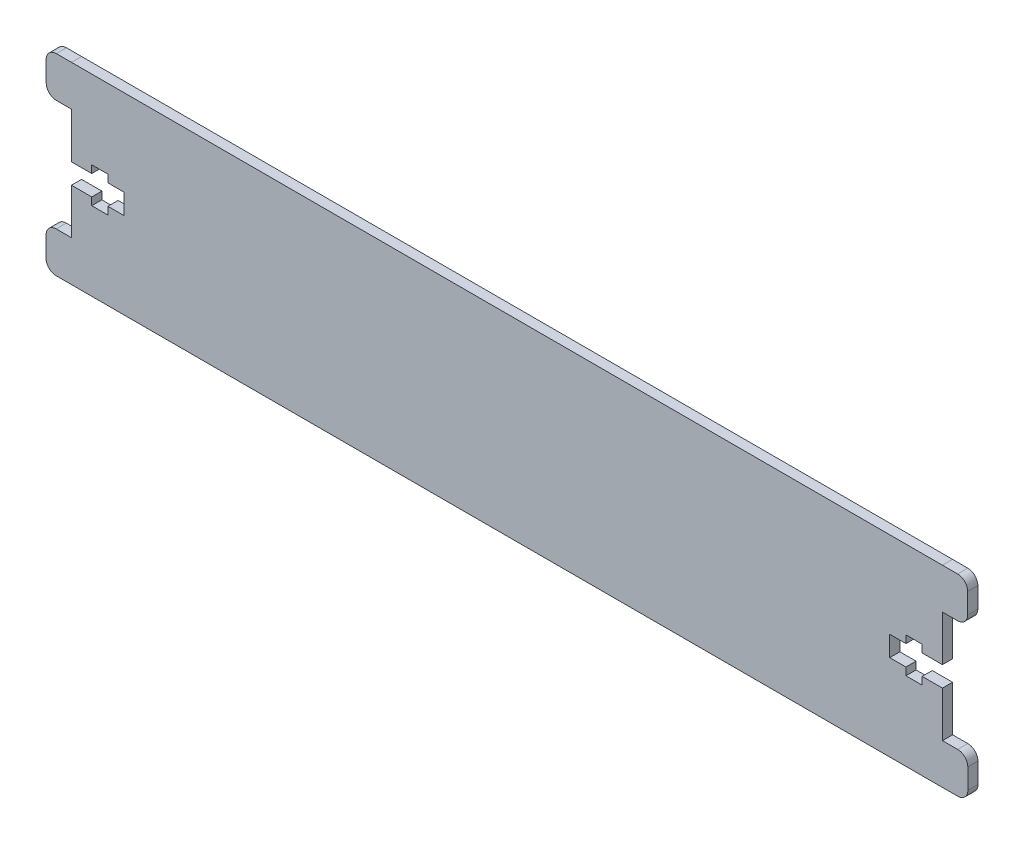
SolidWorks part; units mm, degrees
ref_plane "前视基准面" through (0, 0, 0) normal (0, 0, 1) x (1, 0, 0)
ref_plane "上视基准面" through (0, 0, 0) normal (0, 1, 0) x (1, 0, 0)
ref_plane "右视基准面" through (0, 0, 0) normal (1, 0, 0) x (0, 0, -1)
sketch "草图1" plane through (0, 0, 0) normal (0, 0, 1) x (1, 0, 0)
  line L0 (81.5579, -9.9003) -> (76.5617, -9.9106) construction
  line L1 (81.527, 20.0921) -> (76.5307, 20.0921) construction
  line L2 (81.5436, -5.9003) -> (76.5436, -5.9045)
  line L3 (81.5723, -13.9002) -> (81.5436, -5.9003)
  line L4 (76.5723, -13.9178) -> (81.5723, -13.9002)
  line L5 (66.1319, 5.08) -> (77.8396, 5.0921) construction
  line L6 (76.5319, 7.08) -> (72.5319, 7.08)
  line L7 (72.5319, 7.08) -> (72.5319, 8.58)
  line L8 (72.5319, 8.58) -> (69.3319, 8.58)
  line L9 (69.3319, 8.58) -> (69.3319, 7.08)
  line L10 (69.3319, 7.08) -> (66.1319, 7.08)
  line L11 (69.3319, 1.58) -> (69.3319, 3.08)
  line L12 (72.5319, 3.08) -> (72.5319, 1.58)
  line L13 (69.3319, 3.08) -> (66.1319, 3.08)
  line L14 (72.5319, 1.58) -> (69.3319, 1.58)
  line L15 (76.5436, 3.08) -> (72.5319, 3.08)
  line L16 (76.5331, 24.0993) -> (81.5331, 24.0921)
  line L17 (81.5331, 24.0921) -> (81.5209, 16.0921)
  line L18 (81.5209, 16.0921) -> (76.5209, 16.086)
  line L19 (76.5209, 16.086) -> (76.5319, 7.08)
  line L20 (76.5436, -5.9045) -> (76.5436, 3.08)
  line L21 (76.5319, 7.08) -> (72.5319, 7.08)
  line L22 (72.5319, 8.58) -> (69.3319, 8.58)
  line L23 (76.5319, 7.08) -> (72.5319, 7.08)
  line L24 (72.5319, 7.08) -> (72.5319, 8.58)
  line L25 (72.5319, 8.58) -> (69.3319, 8.58)
  line L26 (69.3319, 8.58) -> (69.3319, 7.08)
  line L27 (69.3319, 7.08) -> (66.1319, 7.08)
  line L28 (69.3319, 1.58) -> (69.3319, 3.08)
  line L29 (72.5319, 3.08) -> (72.5319, 1.58)
  line L30 (69.3319, 3.08) -> (66.1319, 3.08)
  line L31 (72.5319, 1.58) -> (69.3319, 1.58)
  line L32 (76.5436, 3.08) -> (72.5319, 3.08)
  line L33 (69.3319, 7.08) -> (66.1319, 7.08)
  line L34 (72.5319, 7.08) -> (72.5319, 8.58)
  line L35 (69.3319, 8.58) -> (69.3319, 7.08)
  line L36 (69.3319, 3.08) -> (66.1319, 3.08)
  line L37 (69.3319, 1.58) -> (69.3319, 3.08)
  line L38 (72.5319, 1.58) -> (69.3319, 1.58)
  line L39 (72.5319, 3.08) -> (72.5319, 1.58)
  line L40 (76.5436, 3.08) -> (72.5319, 3.08)
  line L41 (76.5331, 24.0993) -> (-95.4669, 24.0993)
  line L43 (-9.4669, 24.0993) -> (-9.4669, -22.62) construction
  line L44 (-85.0657, 5.08) -> (-96.7735, 5.0921) construction
  line L45 (-100.4608, 20.0921) -> (-95.4646, 20.0921) construction
  line L46 (-100.4918, -9.9003) -> (-95.4956, -9.9106) construction
  line L47 (-95.4774, 3.08) -> (-91.4657, 3.08)
  line L48 (-91.4657, 3.08) -> (-91.4657, 1.58)
  line L49 (-91.4657, 1.58) -> (-88.2657, 1.58)
  line L50 (-88.2657, 1.58) -> (-88.2657, 3.08)
  line L51 (-88.2657, 3.08) -> (-85.0657, 3.08)
  line L52 (-85.0657, 3.08) -> (-85.0657, 7.08)
  line L53 (-88.2657, 8.58) -> (-88.2657, 7.08)
  line L54 (-91.4657, 7.08) -> (-91.4657, 8.58)
  line L55 (-88.2657, 7.08) -> (-85.0657, 7.08)
  line L56 (-91.4657, 8.58) -> (-88.2657, 8.58)
  line L57 (-95.4657, 7.08) -> (-91.4657, 7.08)
  line L58 (76.5319, 7.08) -> (72.5319, 7.08)
  line L59 (72.5319, 8.58) -> (69.3319, 8.58)
  line L60 (69.3319, 7.08) -> (66.1319, 7.08)
  line L61 (72.5319, 7.08) -> (72.5319, 8.58)
  line L62 (69.3319, 8.58) -> (69.3319, 7.08)
  line L63 (66.1319, 3.08) -> (66.1319, 7.08)
  line L64 (69.3319, 3.08) -> (66.1319, 3.08)
  line L65 (69.3319, 1.58) -> (69.3319, 3.08)
  line L66 (72.5319, 1.58) -> (69.3319, 1.58)
  line L67 (72.5319, 3.08) -> (72.5319, 1.58)
  line L68 (76.5436, 3.08) -> (72.5319, 3.08)
  line L70 (-95.4774, 3.08) -> (-91.4657, 3.08)
  line L71 (-91.4657, 3.08) -> (-91.4657, 1.58)
  line L72 (-91.4657, 1.58) -> (-88.2657, 1.58)
  line L73 (-88.2657, 1.58) -> (-88.2657, 3.08)
  line L74 (-88.2657, 3.08) -> (-85.0657, 3.08)
  line L76 (-88.2657, 8.58) -> (-88.2657, 7.08)
  line L78 (-91.4657, 7.08) -> (-91.4657, 8.58)
  line L79 (-88.2657, 7.08) -> (-85.0657, 7.08)
  line L81 (-95.4774, 3.08) -> (-91.4657, 3.08)
  line L82 (-91.4657, 1.58) -> (-88.2657, 1.58)
  line L83 (-88.2657, 3.08) -> (-85.0657, 3.08)
  line L84 (-91.4657, 3.08) -> (-91.4657, 1.58)
  line L85 (-88.2657, 1.58) -> (-88.2657, 3.08)
  line L86 (-88.2657, 7.08) -> (-85.0657, 7.08)
  line L87 (-88.2657, 8.58) -> (-88.2657, 7.08)
  line L88 (-91.4657, 8.58) -> (-88.2657, 8.58)
  line L89 (-91.4657, 7.08) -> (-91.4657, 8.58)
  line L90 (-95.4657, 7.08) -> (-91.4657, 7.08)
  line L92 (-91.4657, 8.58) -> (-88.2657, 8.58)
  line L94 (-95.4657, 7.08) -> (-91.4657, 7.08)
  line L95 (-95.4774, -5.9045) -> (-95.4774, 3.08)
  line L97 (-95.4547, 16.086) -> (-95.4657, 7.08)
  line L98 (-100.4547, 16.0921) -> (-95.4547, 16.086)
  line L99 (-100.4669, 24.0921) -> (-100.4547, 16.0921)
  line L100 (-95.4669, 24.0993) -> (-100.4669, 24.0921)
  line L101 (-95.4774, 3.08) -> (-91.4657, 3.08)
  line L102 (-91.4657, 1.58) -> (-88.2657, 1.58)
  line L103 (-88.2657, 3.08) -> (-85.0657, 3.08)
  line L104 (-91.4657, 3.08) -> (-91.4657, 1.58)
  line L105 (-88.2657, 1.58) -> (-88.2657, 3.08)
  line L106 (-88.2657, 7.08) -> (-85.0657, 7.08)
  line L107 (-88.2657, 8.58) -> (-88.2657, 7.08)
  line L108 (-91.4657, 8.58) -> (-88.2657, 8.58)
  line L109 (-91.4657, 7.08) -> (-91.4657, 8.58)
  line L110 (-95.4657, 7.08) -> (-91.4657, 7.08)
  line L111 (-95.5062, -13.9178) -> (-100.5062, -13.9002)
  line L112 (-100.5062, -13.9002) -> (-100.4774, -5.9003)
  line L113 (-100.4774, -5.9003) -> (-95.4774, -5.9045)
  line L114 (-95.5062, -13.9178) -> (76.5723, -13.9178)
  point P4 (66.1319, 5.08)
  dimension "D1" = 172
  dimension "D2" = 7
  dimension "D3" = 4
  dimension "D4" = 8
  dimension "D5" = 4
  dimension "D6" = 3.2
  dimension "D7" = 5
  dimension "D8" = 15
extrude "凸台-拉伸1" add sketch "草图1" along normal blind 2
sketch "草图2" plane through (76.5436, 0, 0) normal (1, 0, 0) x (0, 0, -1)
  line L0 (-1, 3.08) -> (-1, 7.08)
  line L1 (-2, 3.08) -> (0, 3.08) construction
  line L2 (-2, 7.08) -> (0, 7.08) construction
  circle A0 centre (-1, 5.08) radius 2
fillet "圆角1" radius 2 8 edges at (81.5436, -5.9003, 1) (81.5209, 16.0921, 1) (-100.4774, -5.9003, 1) (-100.4547, 16.0921, 1) (-100.5062, -13.9002, 1) (-100.4669, 24.0921, 1) (81.5331, 24.0921, 1) (81.5723, -13.9002, 1)
